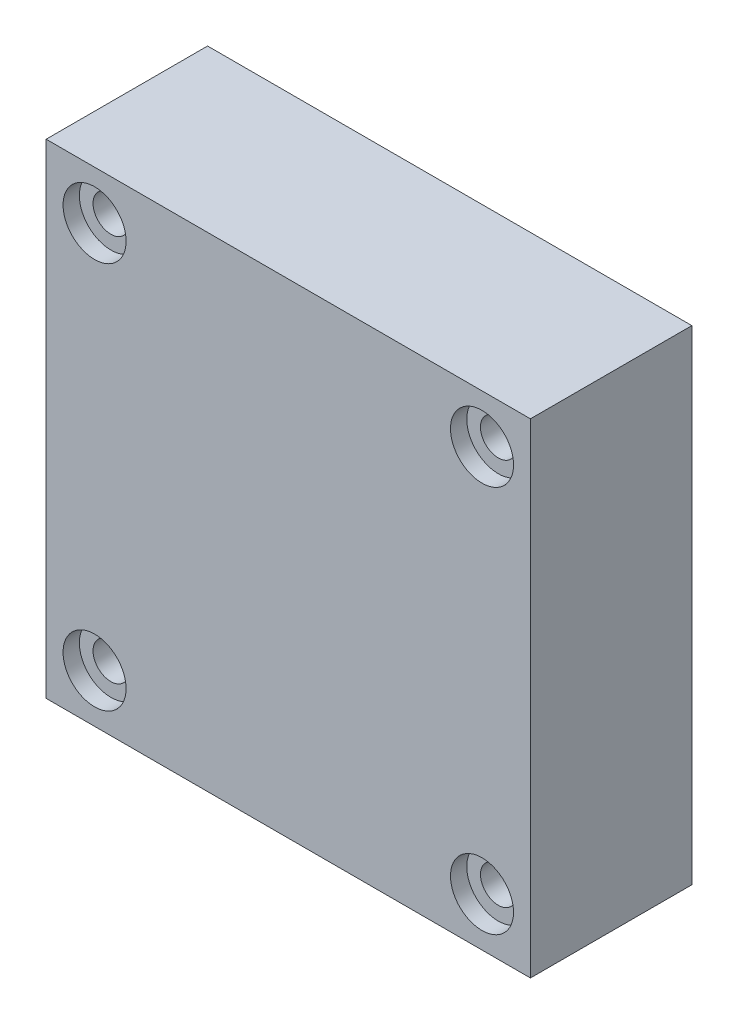
SolidWorks part; units mm, degrees
ref_plane "Front Plane" through (0, 0, 0) normal (0, 0, 1) x (1, 0, 0)
ref_plane "Top Plane" through (0, 0, 0) normal (0, 1, 0) x (1, 0, 0)
ref_plane "Right Plane" through (0, 0, 0) normal (1, 0, 0) x (0, 0, -1)
sketch "Sketch2" plane through (0, 0, 0) normal (0, 0, 1) x (1, 0, 0)
  line L1 (0, 0) -> (76.2, 0)
  line L2 (0, 0) -> (0, 76.2)
  line L3 (0, 76.2) -> (76.2, 76.2)
  line L4 (76.2, 0) -> (76.2, 76.2)
  dimension "D1" = 76.2
  dimension "D2" = 76.2
extrude "Boss-Extrude1" add sketch "Sketch2" along normal blind 25.4
hole_wizard "CBORE for #10 Button Head Cap Screw1" positions "Sketch3" profile "Sketch4" counterbore size "#10" standard "ANSI Inch" end condition through all
sketch "Sketch3" plane through (0, 0, 25.4) normal (0, 0, 1) x (1, 0, 0)
  line L0 (76.2, 76.2) -> (0, 76.2) construction
  line L1 (0, 76.2) -> (0, 0) construction
  line L2 (76.2, 0) -> (76.2, 76.2) construction
  line L3 (0, 0) -> (76.2, 0) construction
  point P0 (7.62, 68.58)
  point P2 (68.58, 68.58)
  point P4 (68.58, 7.62)
  point P6 (7.62, 7.62)
  dimension "D1" = 7.62
  dimension "D2" = 7.62
  dimension "D3" = 7.62
  dimension "D4" = 7.62
  dimension "D5" = 7.62
  dimension "D6" = 7.62
  dimension "D7" = 7.62
  dimension "D8" = 7.62
sketch "Sketch4" plane through (7.62, 68.58, 25.4) normal (1, 0, 0) x (0, -1, 0)
  line L0 (0, 0) -> (0, 25.4)
  line L1 (0, 25.4) -> (2.8067, 25.4)
  line L3 (2.8067, 25.4) -> (2.8067, 2.5654)
  line L4 (2.8067, 2.5654) -> (4.9606, 2.5654)
  line L5 (4.9606, 2.5654) -> (4.9606, 0)
  line L7 (4.9606, 0) -> (0, 0)
  line L11 (0, -6.35) -> (0, 107.95) construction
  dimension "Thru Hole Dia." = 5.6134
  dimension "Thru Hole Depth" = 25.4
  dimension "C'Bore Dia." = 9.9212
  dimension "C'Bore Depth" = 2.5654
